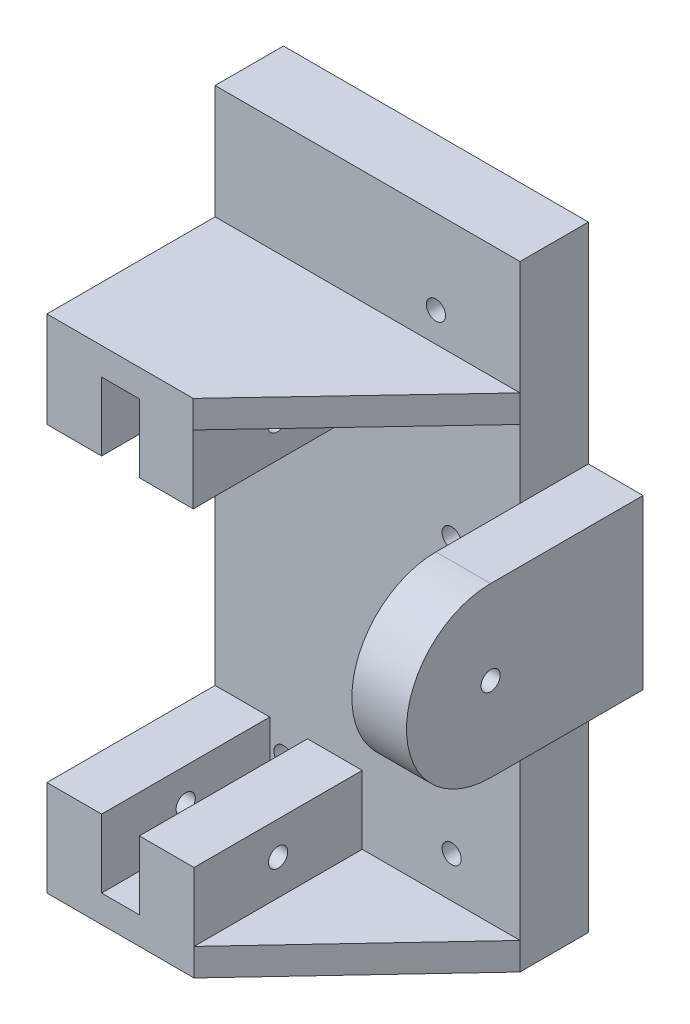
SolidWorks part; units mm, degrees
ref_plane "Plan de face" through (0, 0, 0) normal (0, 0, 1) x (1, 0, 0)
ref_plane "Plan de dessus" through (0, 0, 0) normal (0, 1, 0) x (1, 0, 0)
ref_plane "Plan de droite" through (0, 0, 0) normal (1, 0, 0) x (0, 0, -1)
sketch "Esquisse1" plane through (0, 0, 0) normal (0, 0, 1) x (1, 0, 0)
  line L0 (-6.15, 0) -> (-6.15, -6.15) construction
  line L1 (0, 0) -> (-22.3, 0)
  line L2 (0, 0) -> (0, -43)
  line L3 (0, -43) -> (-22.3, -43)
  line L4 (-22.3, 0) -> (-22.3, -43)
  line L5 (-6.15, -6.15) -> (0, -6.15) construction
  circle A0 centre (-6.15, -6.15) radius 2.45
  dimension "D1" = 22.3
  dimension "D2" = 43
  dimension "D3" = 6.15
  dimension "D4" = 6.15
extrude "Boss.-Extru.1" add sketch "Esquisse1" along normal blind 5
sketch "Esquisse2" plane through (0, 0, 5) normal (0, 0, 1) x (1, 0, 0)
  circle A0 centre (-6.15, -6.15) radius 2.45
  circle A1 centre (-6.15, -6.15) radius 0.7
extrude "Boss.-Extru.2" add sketch "Esquisse2" against normal blind 2.47
sketch "Esquisse3" plane through (0, 0, 5) normal (0, 0, 1) x (1, 0, 0)
  line L0 (-22.3, 0) -> (-22.3, -43) construction
  line L1 (-22.3, -38) -> (-18.3, -38)
  line L2 (-22.3, -38) -> (-22.3, -43)
  line L3 (-22.3, -43) -> (-18.3, -43)
  line L4 (-18.3, -38) -> (-18.3, -43)
  line L5 (-22.3, -43) -> (0, -43) construction
  line L6 (-18.3, -38) -> (-18.3, 0) construction
  line L7 (-15.54, -43) -> (-11.54, -43)
  line L8 (-15.54, -43) -> (-15.54, -38)
  line L9 (-15.54, -38) -> (-11.54, -38)
  line L10 (-11.54, -43) -> (-11.54, -38)
  line L11 (0, 0) -> (-22.3, 0) construction
  line L12 (-15.54, -38) -> (-15.54, 0) construction
  line L13 (-22.3, -15.32) -> (-18.3, -15.32)
  line L14 (-22.3, -15.32) -> (-22.3, -10.32)
  line L15 (-22.3, -10.32) -> (-18.3, -10.32)
  line L16 (-18.3, -15.32) -> (-18.3, -10.32)
  line L17 (-18.3, -15.32) -> (0, -15.32) construction
  line L18 (0, -43) -> (0, 0) construction
  line L19 (-18.3, -10.32) -> (0, -10.32) construction
  line L20 (-15.54, -15.32) -> (-11.6, -15.32)
  line L21 (-15.54, -15.32) -> (-15.54, -10.32)
  line L22 (-15.54, -10.32) -> (-11.6, -10.32)
  line L23 (-11.6, -15.32) -> (-11.6, -10.32)
  line L24 (-18.3, -38) -> (0, -38) construction
  dimension "D1" = 4
  dimension "D2" = 5
  dimension "D3" = 4
  dimension "D4" = 2.76
  dimension "D5" = 22.68
  dimension "D6" = 5
extrude "Boss.-Extru.3" add sketch "Esquisse3" along normal blind 12.3
sketch "Esquisse4" plane through (-22.3, 0, 0) normal (-1, 0, 0) x (0, 0, 1)
  line L0 (5, -10.32) -> (5, -15.32) construction
  line L1 (17.3, -15.32) -> (5, -15.32) construction
  line L2 (5, -15.32) -> (5, -38) construction
  line L3 (5, -38) -> (5, -43) construction
  line L4 (17.3, -43) -> (0, -43) construction
  line L5 (5, -12.82) -> (17.3, -12.82) construction
  line L6 (17.3, -10.32) -> (17.3, -15.32) construction
  line L7 (11.15, -38) -> (11.15, -43) construction
  line L9 (17.3, -38) -> (5, -38) construction
  circle A0 centre (11.15, -12.82) radius 0.7
  circle A1 centre (11.15, -40.42) radius 0.7
  dimension "D1" = 27.6
extrude "Enlèv. mat.-Extru.1" cut sketch "Esquisse4" against normal through all
sketch "Esquisse5" plane through (0, -43, 0) normal (0, -1, 0) x (1, 0, 0)
  line L0 (-22.3, 17.3) -> (-11.54, 17.3)
  line L1 (-11.54, 17.3) -> (0, 5)
  line L2 (0, 5) -> (0, 0)
  line L3 (0, 0) -> (-22.3, 0)
  line L4 (-22.3, 0) -> (-22.3, 17.3)
extrude "Boss.-Extru.4" add sketch "Esquisse5" along normal blind 2
sketch "Esquisse6" plane through (0, -10.32, 0) normal (0, 1, 0) x (1, 0, 0)
  line L0 (-22.3, -5) -> (-22.3, -17.3)
  line L1 (-22.3, -17.3) -> (-11.6, -17.3)
  line L2 (-11.6, -17.3) -> (0, -5)
  line L3 (0, -5) -> (-22.3, -5)
extrude "Boss.-Extru.5" add sketch "Esquisse6" along normal blind 2
sketch "Esquisse7" plane through (0, 0, 0) normal (1, 0, 0) x (0, 0, -1)
  line L0 (0, -21.47) -> (-11.15, -21.47) construction
  line L1 (0, -45) -> (0, 0) construction
  line L3 (-5, -15.32) -> (0, -15.32) construction
  line L4 (0, -27.62) -> (-5, -27.62) construction
  line L5 (-5, -43) -> (-5, -10.32) construction
  line L6 (-11.15, -21.47) -> (-11.15, -15.32) construction
  line L7 (-11.15, -15.32) -> (0, -15.32)
  line L8 (0, -15.32) -> (0, -27.62)
  line L9 (0, -27.62) -> (-11.15, -27.62)
  arc A0 (-11.15, -27.62) -> (-11.15, -15.32) centre (-11.15, -21.47) cw
  circle A1 centre (-11.15, -21.47) radius 0.7
  dimension "D1" = 6.15
  dimension "D2" = 11.15
  dimension "D3" = 6.15
extrude "Boss.-Extru.6" add sketch "Esquisse7" along normal blind 4
sketch "Esquisse8" plane through (0, 0, 0) normal (0, 0, -1) x (-1, 0, 0)
  line L1 (22.3, -45) -> (0, -45) construction
  line L2 (22.3, -45) -> (22.3, -15) construction
  line L3 (22.3, -15) -> (0, -15) construction
  line L4 (0, -45) -> (0, -15) construction
  line L6 (11.15, -45) -> (11.15, -15) construction
  line L7 (22.3, -30) -> (0, -30) construction
  circle A0 centre (17.3, -40) radius 0.7
  circle A1 centre (5, -40) radius 0.7
  circle A2 centre (5, -20) radius 0.7
  circle A3 centre (17.3, -20) radius 0.7
  dimension "D2" = 5
  dimension "D1" = 30
  dimension "D3" = 5
extrude "Enlèv. mat.-Extru.3" cut sketch "Esquisse8" against normal through all
